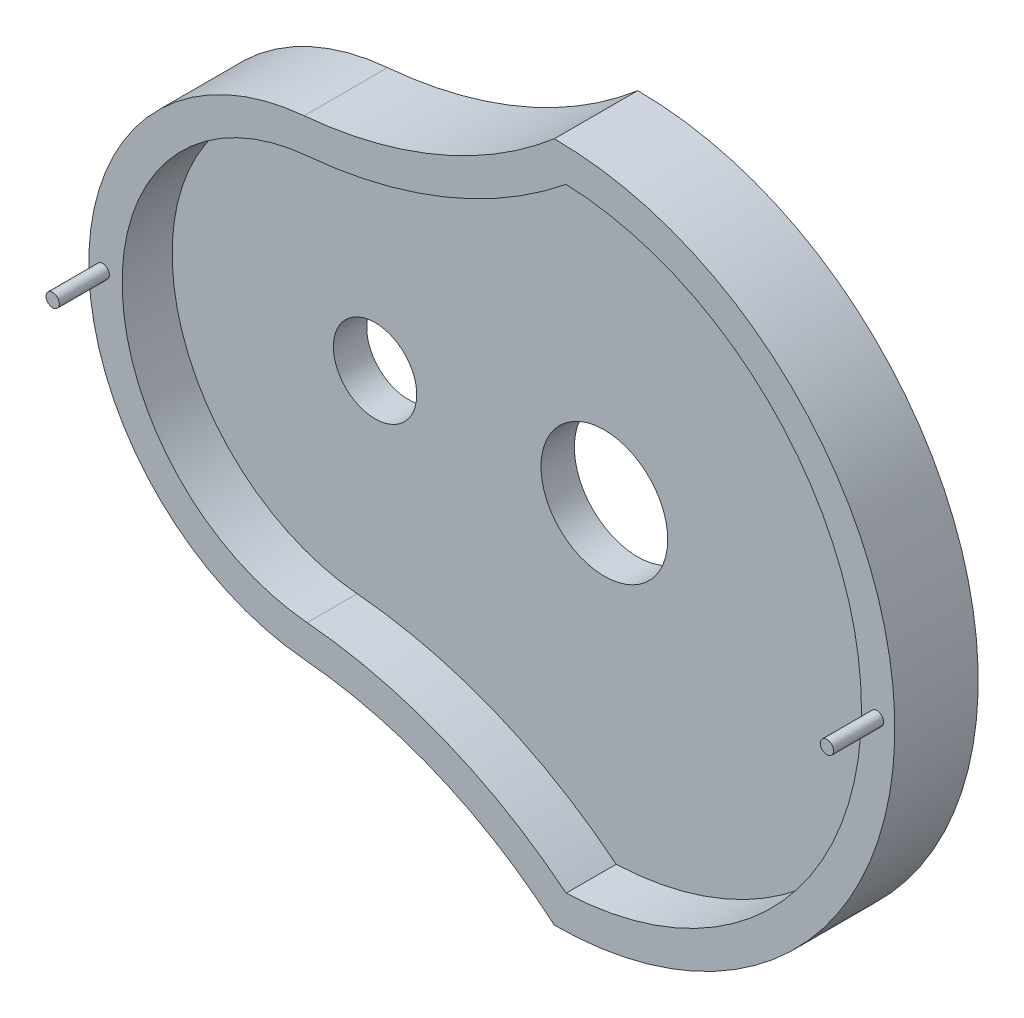
SolidWorks part; units mm, degrees
ref_plane "Front Plane" through (0, 0, 0) normal (0, 0, 1) x (1, 0, 0)
ref_plane "Top Plane" through (0, 0, 0) normal (0, 1, 0) x (1, 0, 0)
ref_plane "Right Plane" through (0, 0, 0) normal (1, 0, 0) x (0, 0, -1)
sketch "Sketch1" plane through (0, 0, 0) normal (0, 0, 1) x (1, 0, 0)
  arc A0 (0, -25.9296) -> (0, 25.9296) centre (0, 0) ccw
  arc A1 (-19.05, 17.9219) -> (-19.05, -17.9219) centre (-17.4625, 0) ccw
  arc A2 (-19.05, 17.9219) -> (0, 25.9296) centre (-22.0424, 51.7042) ccw
  arc A3 (-19.05, -17.9219) -> (0, -25.9296) centre (-22.0424, -51.7042) cw
  point P8 (0, 0)
  point P9 (0, 0)
  point P10 (0, 0)
  point P12 (0, 0)
  point P13 (0, 0)
  point P14 (0, 0)
  dimension "D1" = 35.9842
  dimension "D2" = 51.8592
  dimension "D3" = 17.4625
  dimension "D4" = 19.05
  dimension "D5" = 19.05
extrude "Boss-Extrude1" add sketch "Sketch1" along normal blind 6.35
shell "Shell1" thickness 2.54
sketch "Sketch2" plane through (0, 0, 6.35) normal (0, 0, 1) x (1, 0, 0)
  circle A0 centre (-34.3927, 0) radius 0.508
  circle A1 centre (24.5691, 0) radius 0.508
  dimension "D1" = 1.016
extrude "Boss-Extrude2" add sketch "Sketch2" along normal blind 3.81
sketch "Sketch3" plane through (0, 0, 2.54) normal (0, 0, 1) x (1, 0, 0)
  circle A0 centre (0, 0) radius 4.826
  circle A1 centre (-17.4625, 0) radius 3.175
  point P5 (0, 0)
  point P6 (0, 0)
  dimension "D2" = 9.652
  dimension "D3" = 6.35
  dimension "D1" = 17.4625
extrude "Cut-Extrude1" cut sketch "Sketch3" against normal up to surface (2.54 mm away) up to face at (-6.8314, 0, 0)
equation "\"Input Gear OD\"= 0.4167in"
equation "\"Output Gear OD\"= 1.0417in"
equation "\"Input Gear Housing OD\"= \"Input Gear OD\" + 1"
equation "\"Output Gear Housing OD\"= \"Output Gear OD\" + 1"
equation "\"Inside Journal Bearong OD\"= 0.25in"
equation "\"Outside Journal Bearing OD\"= 0.38in"
equation "\"Gear Distance\"= 11 / 16"
equation "\"Thickness of Gear\"= 1 / 8"
equation "\"Pin Length\"= 0.15"
equation "\"Thickness of Part\"= 0.0075"
equation "\"D1@Sketch1\"=\"Input Gear Housing OD\""
equation "\"D2@Sketch1\"=\"Output Gear Housing OD\""
equation "\"D3@Sketch1\"=\"Gear Distance\""
equation "\"D1@Boss-Extrude1\"=\"Thickness of Gear\" * 2"
equation "\"D1@Boss-Extrude2\"=\"Pin Length\""
equation "\"D1@Sketch3\"=\"Gear Distance\""
equation "\"D2@Sketch3\"=\"Outside Journal Bearing OD\""
equation "\"D3@Sketch3\"=\"Inside Journal Bearong OD\""
